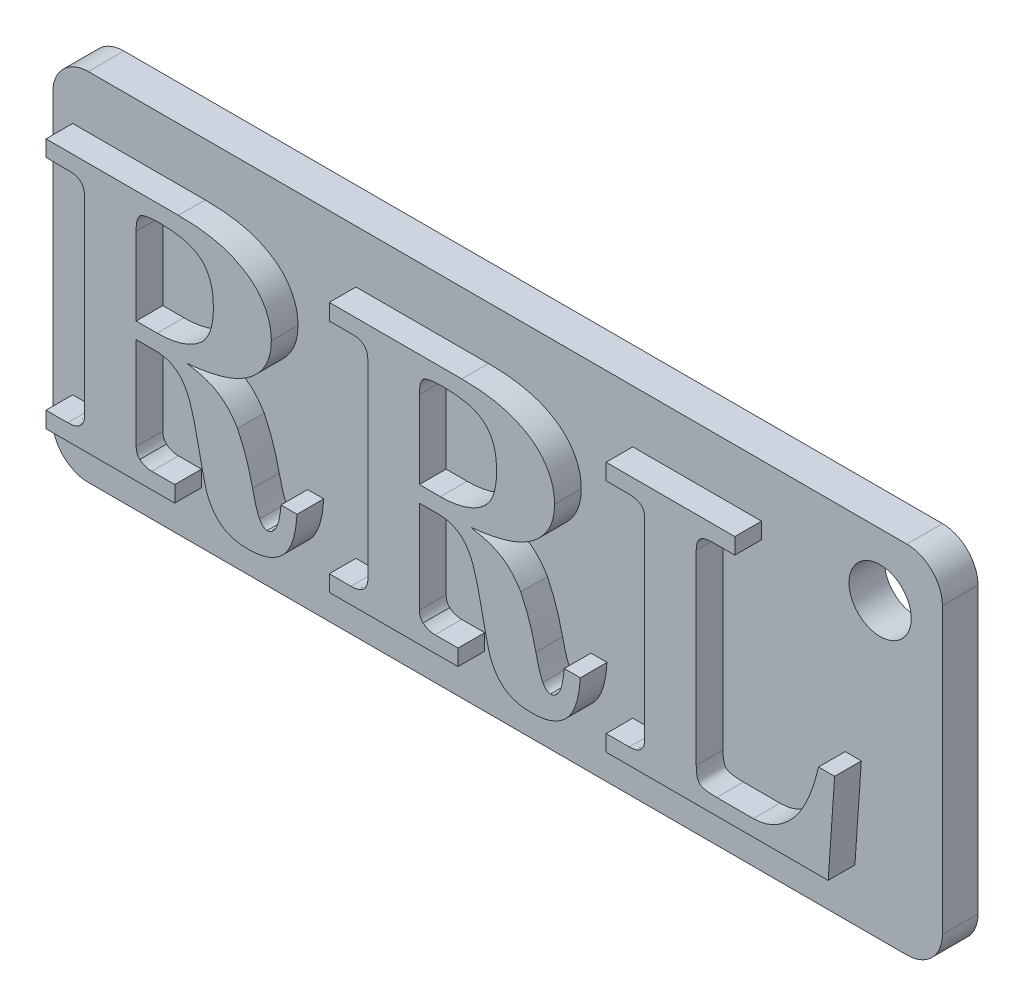
SolidWorks part; units mm, degrees
ref_plane "Front Plane" through (0, 0, 0) normal (0, 0, 1) x (1, 0, 0)
ref_plane "Top Plane" through (0, 0, 0) normal (0, 1, 0) x (1, 0, 0)
ref_plane "Right Plane" through (0, 0, 0) normal (1, 0, 0) x (0, 0, -1)
sketch "Sketch2" plane through (0, 0, 0) normal (0, 0, 1) x (1, 0, 0)
  line L1 (-23, 10) -> (23, 10)
  line L2 (-25, 8) -> (-25, -8)
  line L3 (-23, -10) -> (23, -10)
  line L4 (25, 8) -> (25, -8)
  line L5 (-25, 10) -> (25, -10) construction
  line L6 (-25, -10) -> (25, 10) construction
  arc A0 (23, 10) -> (25, 8) centre (23, 8) cw
  arc A1 (23, -10) -> (25, -8) centre (23, -8) ccw
  arc A2 (-25, -8) -> (-23, -10) centre (-23, -8) ccw
  arc A3 (-23, 10) -> (-25, 8) centre (-23, 8) ccw
  point P0 (0, 0)
  dimension "D3" = 2
  dimension "D1" = 50
  dimension "D2" = 20
extrude "Boss-Extrude2" add sketch "Sketch2" along normal blind 2
sketch "Sketch1" plane through (0, 0, 2) normal (0, 0, 1) x (1, 0, 0)
  line L0 (180, 540) -> (900, 540) construction
  text T0 "RRL" font "Century Schoolbook" height in points 54
extrude "Boss-Extrude1" add sketch "Sketch1" along normal blind 1.5
sketch "Sketch3" plane through (0, 0, 2) normal (0, 0, 1) x (1, 0, 0)
  line L0 (25, -8) -> (25, 8) construction
  line L1 (23, 10) -> (-23, 10) construction
  circle A0 centre (21.5, 6.5) radius 1.75
  dimension "D1" = 3.5
  dimension "D2" = 3.5
  dimension "D3" = 3.5
extrude "Cut-Extrude1" cut sketch "Sketch3" against normal through all
